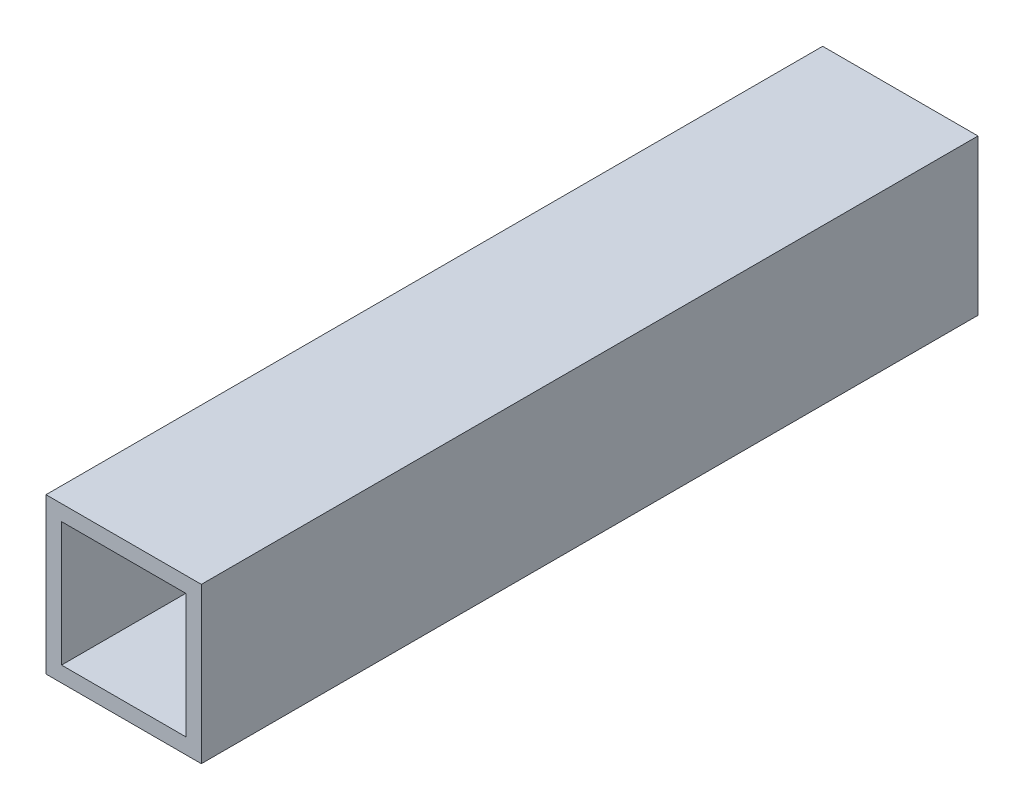
SolidWorks part; units mm, degrees
ref_plane "Front Plane" through (0, 0, 0) normal (0, 0, 1) x (1, 0, 0)
ref_plane "Top Plane" through (0, 0, 0) normal (0, 1, 0) x (1, 0, 0)
ref_plane "Right Plane" through (0, 0, 0) normal (1, 0, 0) x (0, 0, -1)
sketch "Sketch1" plane through (0, 0, 0) normal (0, 0, 1) x (1, 0, 0)
  line L0 (-20, 20) -> (-20, -20)
  line L1 (-25, 25) -> (25, 25)
  line L2 (-25, 25) -> (-25, -25)
  line L3 (-25, -25) -> (25, -25)
  line L4 (25, 25) -> (25, -25)
  line L5 (-20, -20) -> (20, -20)
  line L6 (20, 20) -> (20, -20)
  line L7 (-20, 20) -> (20, 20)
  dimension "tube_width" = 50
  dimension "D1" = 50
  dimension "D3" = 25
  dimension "D4" = 25
  dimension "tube_thickness" = 5
extrude "Boss-Extrude1" add sketch "Sketch1" along normal blind 175 and the other way blind 75
sketch "Sketch3" plane through (25, 0, 0) normal (1, 0, 0) x (0, 0, -1)
  text T0 "<r90>x</r>" font "Century Gothic" height 40
sketch "Sketch4" plane through (25, 0, 0) normal (1, 0, 0) x (0, 0, -1)
  line L0 (75, -25) -> (75, 25) construction
  point P0 (50, 0)
  dimension "D1" = 25
hole_wizard "Ø25.0mm Dowel Hole1" positions "Sketch5" profile "Sketch6" hole size "Ø25.0" standard "ANSI Metric"
sketch "Sketch5" plane through (25, 0, 0) normal (1, 0, 0) x (0, 0, -1)
  point P0 (50, 0)
sketch "Sketch6" plane through (25, 0, -50) normal (0, 1, 0) x (0, 0, -1)
  line L0 (0, 0) -> (0, 50)
  line L1 (0, 50) -> (12.5, 50)
  line L2 (12.5, 50) -> (12.5, 0)
  line L5 (12.5, 0) -> (0, 0)
  line L11 (0, -6.35) -> (0, 107.95) construction
  dimension "Thru Hole Dia." = 25
  dimension "Thru Hole Depth" = 50
equation "\"D1@Sketch1\"= \"tube_width@Sketch1\""
equation "\"D3@Sketch1\"=\"tube_width@Sketch1\"/2"
equation "\"D4@Sketch1\"=\"tube_width@Sketch1\"/2"
